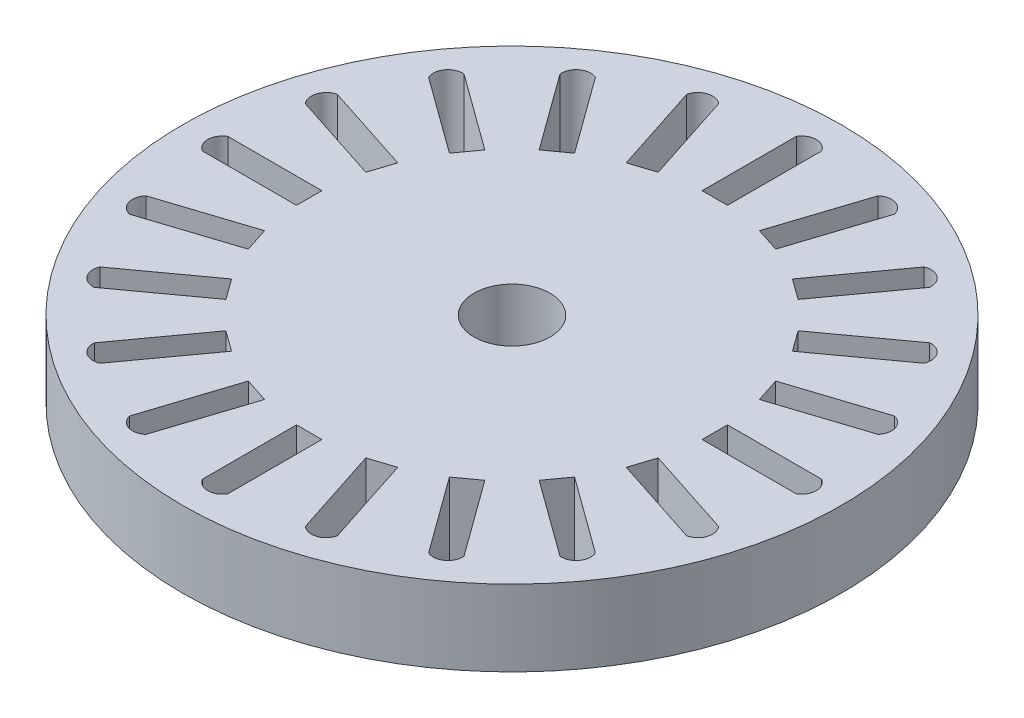
SolidWorks part; units mm, degrees
ref_plane "Alzado" through (0, 0, 0) normal (0, 0, 1) x (1, 0, 0)
ref_plane "Planta" through (0, 0, 0) normal (0, 1, 0) x (1, 0, 0)
ref_plane "Vista lateral" through (0, 0, 0) normal (1, 0, 0) x (0, 0, -1)
sketch "Croquis1" plane through (0, 0, 0) normal (0, 1, 0) x (1, 0, 0)
  circle A0 centre (0, 0) radius 1.5
  circle A1 centre (0, 0) radius 13
  dimension "D1" = 3
  dimension "D2" = 26
extrude "Saliente-Extruir1" add sketch "Croquis1" along normal blind 3
sketch "Croquis2" plane through (0, 3, 0) normal (0, 1, 0) x (1, 0, 0)
  line L0 (-0.5, 8) -> (0.5, 8)
  line L1 (0.5, 8) -> (0.5, 11.7127)
  line L2 (-0.5, 8) -> (-0.5, 11.7131)
  arc A0 (-0.5, 11.7131) -> (0.5, 11.7127) centre (-0.0001, 11.4211) cw
  circle A1 centre (0, 0) radius 13 construction
  circle A2 centre (0, 0) radius 13 construction
  point P5 (0, 0)
  point P6 (0, 0)
  point P10 (0.0001, 12)
  point P11 (0, 8)
  point P12 (0, 11.4211)
  point P13 (0, 0)
  point P14 (0, 0)
  point P15 (0, 0)
  point P16 (0, 0)
  dimension "D2" = 0.5789
  dimension "D4" = 12
  dimension "D1" = 1
  dimension "D3" = 4
  dimension "D5" = 11.4211
extrude "Cortar-Extruir1" cut sketch "Croquis2" against normal up to surface (3 mm away) up to face at (0, 0, 13)
pattern_circular "MatrizC1" count 20 every 18 about axis through (0, 0, 0) along (0, 1, 0) of "Cortar-Extruir1"
